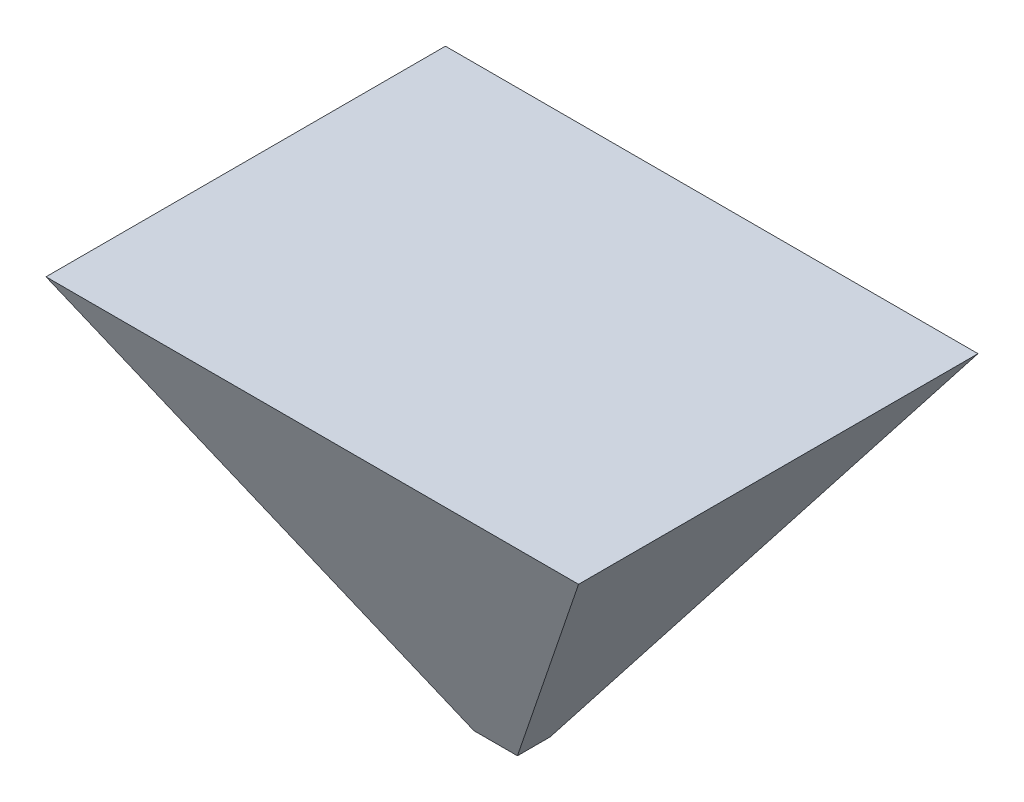
SolidWorks part; units mm, degrees
material "Perspex (TM) GS Acrylic Cast Sheet"
ref_plane "Front Plane" through (0, 0, 0) normal (0, 0, 1) x (1, 0, 0)
ref_plane "Top Plane" through (0, 0, 0) normal (0, 1, 0) x (1, 0, 0)
ref_plane "Right Plane" through (0, 0, 0) normal (1, 0, 0) x (0, 0, -1)
sketch "Sketch1" plane through (0, 0, 0) normal (0, 1, 0) x (1, 0, 0)
  line L1 (-1.8, -1.35) -> (1.8, -1.35)
  line L2 (-1.8, -1.35) -> (-1.8, 1.35)
  line L3 (-1.8, 1.35) -> (1.8, 1.35)
  line L4 (1.8, -1.35) -> (1.8, 1.35)
  line L5 (-1.8, -1.35) -> (1.8, 1.35) construction
  line L6 (-1.8, 1.35) -> (1.8, -1.35) construction
  point P0 (0, 0)
  dimension "D1" = 3.6
  dimension "D2" = 2.7
sketch "Sketch2" plane through (0, 0, 0) normal (0, 0, 1) x (1, 0, 0)
  line L0 (0, 0) -> (0, 30)
  line L1 (0, 30) -> (-22.0353, 30)
  line L2 (-22.0353, 30) -> (-1.8, 0)
  line L3 (-1.8, 0) -> (1.8, 0) construction
  line L4 (-1.8, 0) -> (1.8, 0) construction
  line L5 (-1.8, 0) -> (0, 0)
  point P3 (0, 0)
  point P10 (-1.8, 0)
  point P11 (-21.3817, 30)
  point P12 (0, 0)
  point P14 (0, 0)
  dimension "D1" = 30
  dimension "D2" = 34
ref_plane "Plane2" through (0, 30, 0) normal (0, 1, 0) x (1, 0, 0)
sketch "Sketch5" plane through (0, 30, 0) normal (0, 1, 0) x (1, 0, 0)
  line L1 (22.0353, -16.5264) -> (-22.0353, -16.5264)
  line L2 (22.0353, -16.5264) -> (22.0353, 16.5264)
  line L3 (22.0353, 16.5264) -> (-22.0353, 16.5264)
  line L4 (-22.0353, -16.5264) -> (-22.0353, 16.5264)
  line L5 (22.0353, -16.5264) -> (-22.0353, 16.5264) construction
  line L6 (22.0353, 16.5264) -> (-22.0353, -16.5264) construction
  point P0 (0, 0)
loft "Loft2" add profiles "Sketch1", "Sketch5"
